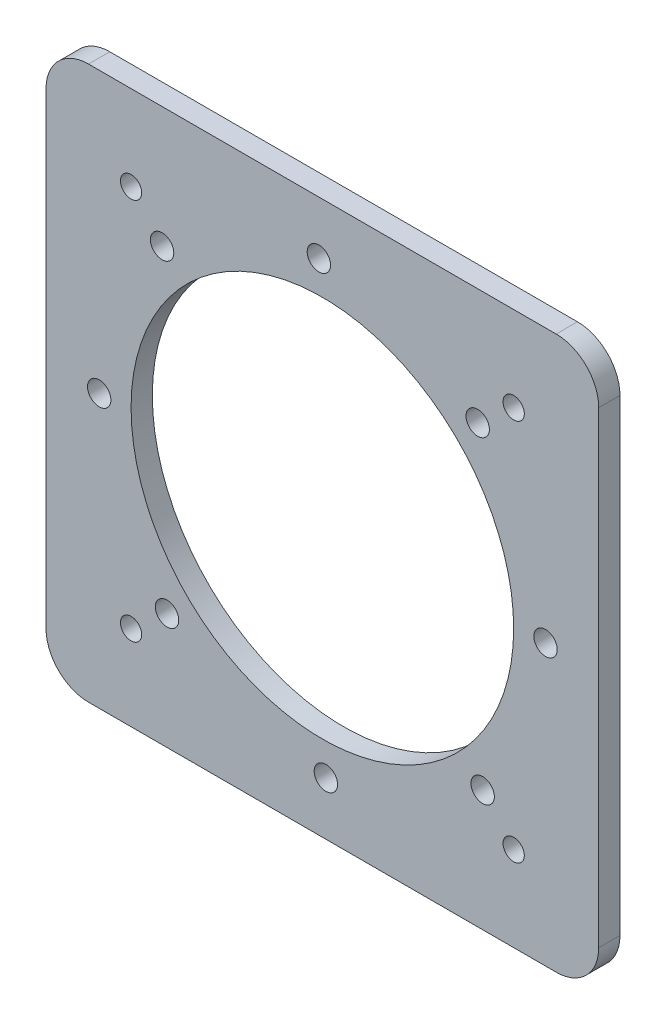
SolidWorks part; units mm, degrees
material "Thornel Mat VMA"
ref_plane "前视基准面" through (0, 0, 0) normal (0, 0, 1) x (1, 0, 0)
ref_plane "上视基准面" through (0, 0, 0) normal (0, 1, 0) x (1, 0, 0)
ref_plane "右视基准面" through (0, 0, 0) normal (1, 0, 0) x (0, 0, -1)
other "Configuration Table"
sketch "草图1" plane through (0, 0, 0) normal (0, 0, 1) x (1, 0, 0)
  line L1 (-65, 65) -> (65, 65)
  line L2 (-65, 65) -> (-65, -65)
  line L3 (-65, -65) -> (65, -65)
  line L4 (65, 65) -> (65, -65)
  line L5 (-65, 65) -> (65, -65) construction
  line L6 (-65, -65) -> (65, 65) construction
  point P0 (0, 0)
  dimension "D1" = 130
  dimension "D2" = 130
extrude "凸台-拉伸1" add sketch "草图1" along normal blind 5
sketch "草图5" plane through (0, 0, 0) normal (0, 0, -1) x (-1, 0, 0)
  circle A0 centre (0, 0) radius 45
  dimension "D1" = 90
extrude "切除-拉伸2" cut sketch "草图5" against normal up to next
fillet "圆角1" radius 10 4 edges at (65, 65, 2.5) (65, -65, 2.5) (-65, -65, 2.5) (-65, 65, 2.5)
sketch "草图6" plane through (0, 0, 0) normal (0, 0, -1) x (-1, 0, 0)
  arc A6 (39.6758, 38.4499) -> (35.7262, 34.6223) centre (37.701, 36.5361) ccw
  arc A7 (35.7262, 34.6223) -> (39.6758, 38.4499) centre (37.701, 36.5361) ccw
  arc A8 (39.6758, 38.4499) -> (35.7262, 34.6223) centre (37.701, 36.5361) ccw
  arc A9 (35.7262, 34.6223) -> (39.6758, 38.4499) centre (37.701, 36.5361) ccw
  arc A10 (54.4684, 1.0901) -> (50.5187, -2.7375) centre (52.4935, -0.8237) ccw
  arc A11 (50.5187, -2.7375) -> (54.4684, 1.0901) centre (52.4935, -0.8237) ccw
  arc A12 (54.4684, 1.0901) -> (50.5187, -2.7375) centre (52.4935, -0.8237) ccw
  arc A13 (50.5187, -2.7375) -> (54.4684, 1.0901) centre (52.4935, -0.8237) ccw
  arc A14 (38.5109, -35.7872) -> (34.5613, -39.6148) centre (36.5361, -37.701) ccw
  arc A15 (34.5613, -39.6148) -> (38.5109, -35.7872) centre (36.5361, -37.701) ccw
  arc A16 (38.5109, -35.7872) -> (34.5613, -39.6148) centre (36.5361, -37.701) ccw
  arc A17 (34.5613, -39.6148) -> (38.5109, -35.7872) centre (36.5361, -37.701) ccw
  arc A18 (1.1511, -50.5797) -> (-2.7985, -54.4073) centre (-0.8237, -52.4935) ccw
  arc A19 (-2.7985, -54.4073) -> (1.1511, -50.5797) centre (-0.8237, -52.4935) ccw
  arc A20 (1.1511, -50.5797) -> (-2.7985, -54.4073) centre (-0.8237, -52.4935) ccw
  arc A21 (-2.7985, -54.4073) -> (1.1511, -50.5797) centre (-0.8237, -52.4935) ccw
  arc A22 (-35.7262, -34.6223) -> (-39.6758, -38.4499) centre (-37.701, -36.5361) ccw
  arc A23 (-39.6758, -38.4499) -> (-35.7262, -34.6223) centre (-37.701, -36.5361) ccw
  arc A24 (-35.7262, -34.6223) -> (-39.6758, -38.4499) centre (-37.701, -36.5361) ccw
  arc A25 (-39.6758, -38.4499) -> (-35.7262, -34.6223) centre (-37.701, -36.5361) ccw
  arc A26 (-50.5187, 2.7375) -> (-54.4684, -1.0901) centre (-52.4935, 0.8237) ccw
  arc A27 (-54.4684, -1.0901) -> (-50.5187, 2.7375) centre (-52.4935, 0.8237) ccw
  arc A28 (-50.5187, 2.7375) -> (-54.4684, -1.0901) centre (-52.4935, 0.8237) ccw
  arc A29 (-54.4684, -1.0901) -> (-50.5187, 2.7375) centre (-52.4935, 0.8237) ccw
  arc A30 (-34.5613, 39.6148) -> (-38.5109, 35.7872) centre (-36.5361, 37.701) ccw
  arc A31 (-38.5109, 35.7872) -> (-34.5613, 39.6148) centre (-36.5361, 37.701) ccw
  arc A32 (-34.5613, 39.6148) -> (-38.5109, 35.7872) centre (-36.5361, 37.701) ccw
  arc A33 (-38.5109, 35.7872) -> (-34.5613, 39.6148) centre (-36.5361, 37.701) ccw
  arc A34 (2.7985, 54.4073) -> (-1.1511, 50.5797) centre (0.8237, 52.4935) ccw
  arc A35 (-1.1511, 50.5797) -> (2.7985, 54.4073) centre (0.8237, 52.4935) ccw
  arc A36 (2.7985, 54.4073) -> (-1.1511, 50.5797) centre (0.8237, 52.4935) ccw
  arc A37 (-1.1511, 50.5797) -> (2.7985, 54.4073) centre (0.8237, 52.4935) ccw
  dimension "D2" = 0
  dimension "D3" = 0
  dimension "D4" = 0
  dimension "D5" = 0
  dimension "D6" = 0
  dimension "D7" = 0
  dimension "D8" = 0
  dimension "D9" = 0
extrude "切除-拉伸3" cut sketch "草图6" against normal blind 10
sketch "草图7" plane through (0, 0, 5) normal (0, 0, 1) x (1, 0, 0)
  line L0 (55, 65) -> (-55, 65) construction
  line L1 (-65, 55) -> (-65, -55) construction
  circle A7 centre (-45, 45) radius 2.5
  circle A8 centre (45, 45) radius 2.5
  circle A9 centre (45, -45) radius 2.5
  circle A10 centre (-45, -45) radius 2.5
  dimension "D1" = 5
  dimension "D2" = 20
  dimension "D3" = 20
  dimension "D4" = 2
  dimension "D5" = 2
extrude "切除-拉伸4" cut sketch "草图7" against normal through all
